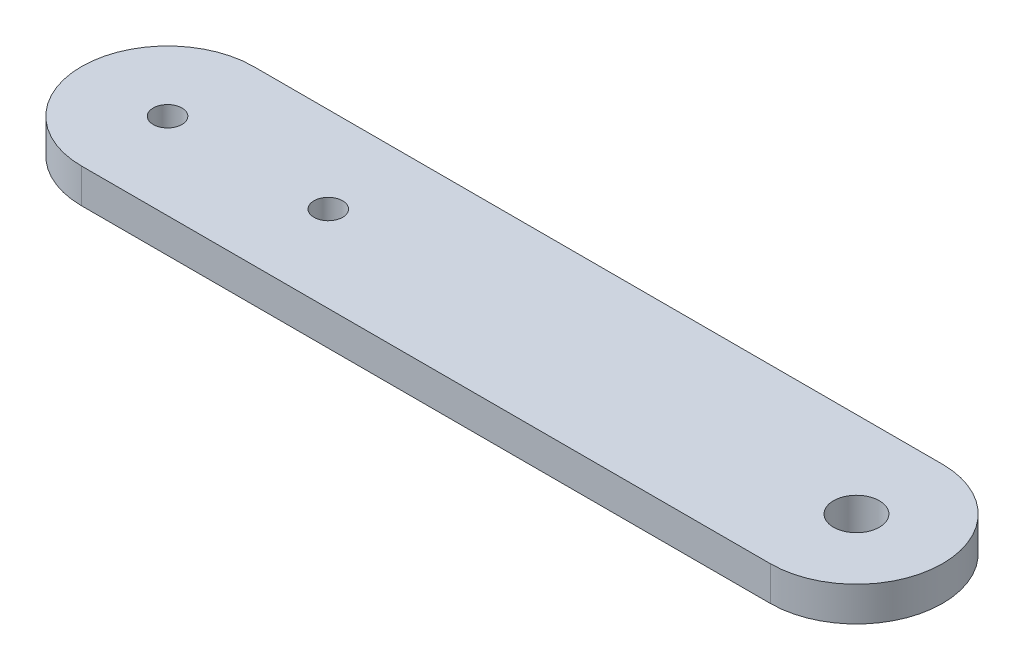
SolidWorks part; units mm, degrees
ref_plane "Front Plane" through (0, 0, 0) normal (0, 0, 1) x (1, 0, 0)
ref_plane "Top Plane" through (0, 0, 0) normal (0, 1, 0) x (1, 0, 0)
ref_plane "Right Plane" through (0, 0, 0) normal (1, 0, 0) x (0, 0, -1)
sketch "Sketch1" plane through (0, 0, 0) normal (0, 1, 0) x (1, 0, 0)
  line L0 (0, 0) -> (60, 0) construction
  line L1 (0, 7.5) -> (60, 7.5)
  line L2 (0, -7.5) -> (60, -7.5)
  arc A0 (0, 7.5) -> (0, -7.5) centre (0, 0) ccw
  arc A1 (60, -7.5) -> (60, 7.5) centre (60, 0) ccw
  circle A2 centre (60, 0) radius 2
  circle A3 centre (0, 0) radius 1.25
  circle A4 centre (14, 0) radius 1.25
  point P3 (30, 0)
  dimension "D2" = 4
  dimension "D3" = 7.5
  dimension "D4" = 2.5
  dimension "D5" = 2.5
  dimension "D1" = 60
  dimension "D6" = 14
extrude "Boss-Extrude1" add sketch "Sketch1" along normal blind 3
